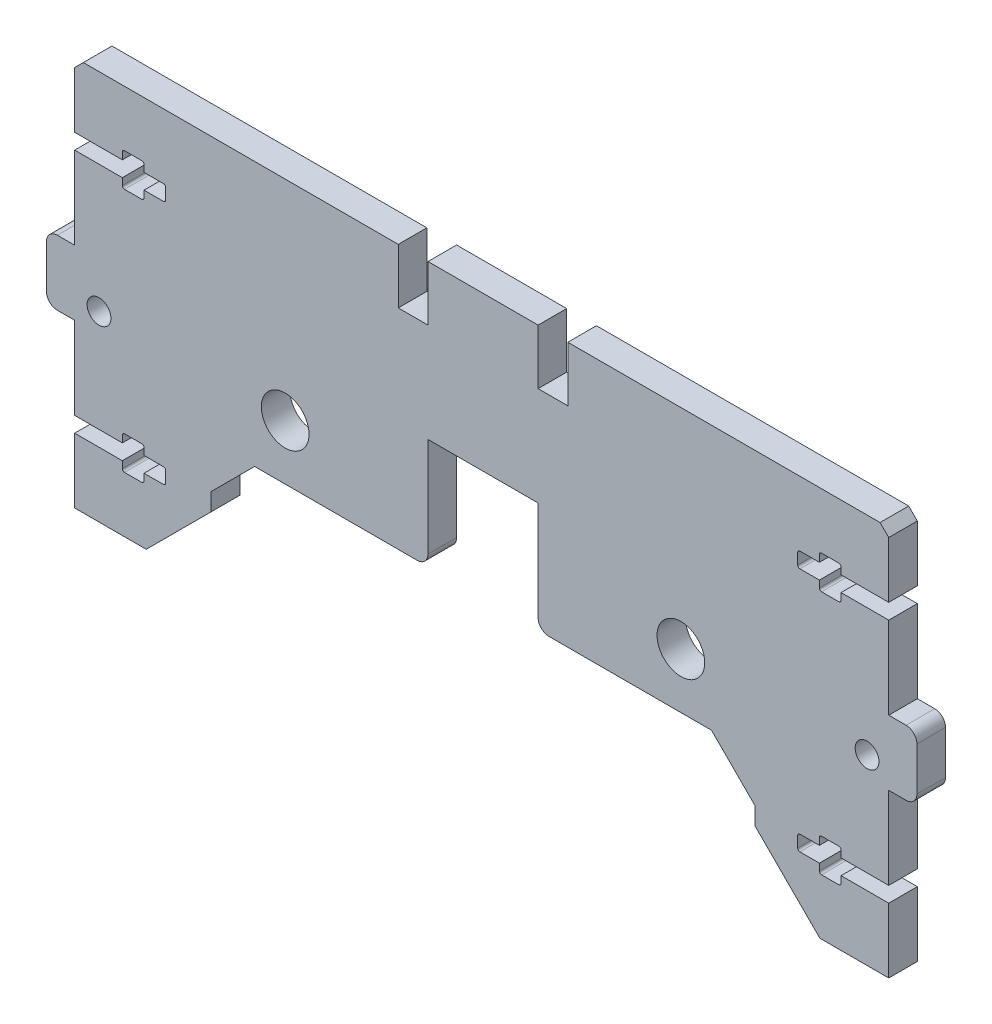
SolidWorks part; units mm, degrees
ref_plane "Front Plane" through (0, 0, 0) normal (0, 0, 1) x (1, 0, 0)
ref_plane "Top Plane" through (0, 0, 0) normal (0, 1, 0) x (1, 0, 0)
ref_plane "Right Plane" through (0, 0, 0) normal (1, 0, 0) x (0, 0, -1)
sketch "Model" plane through (0, 0, 0) normal (0, 0, 1) x (1, 0, 0)
  line L0 (146.91, 29.0548) -> (156.91, 19.0548)
  line L1 (146.91, 29.0548) -> (109.41, 29.0548)
  line L2 (106.91, 54.4548) -> (106.91, 31.5548)
  line L3 (81.51, 54.4548) -> (106.91, 54.4548)
  line L4 (81.51, 54.4548) -> (81.51, 31.5548)
  line L5 (79.01, 29.0548) -> (41.51, 29.0548)
  line L6 (31.51, 19.0548) -> (41.51, 29.0548)
  line L7 (31.51, 19.0548) -> (31.51, 15)
  line L8 (16.51, 0) -> (31.51, 15)
  line L9 (0, 0) -> (16.51, 0)
  line L10 (0, 14.95) -> (0, 0)
  line L11 (0, 14.95) -> (11, 14.95)
  line L12 (11, 14.95) -> (11, 13.365)
  line L13 (11.5, 12.865) -> (15.5, 12.865)
  line L14 (16, 13.365) -> (16, 14.95)
  line L15 (16, 14.95) -> (20.5, 14.95)
  line L16 (21, 15.45) -> (21, 18)
  line L17 (20.5, 18.5) -> (16, 18.5)
  line L18 (16, 18.5) -> (16, 20.085)
  line L19 (15.5, 20.585) -> (11.5, 20.585)
  line L20 (11, 20.085) -> (11, 18.5)
  line L21 (11, 18.5) -> (0, 18.5)
  line L22 (0, 37.5) -> (0, 18.5)
  line L23 (-4, 37.5) -> (0, 37.5)
  line L24 (-6.5, 50) -> (-6.5, 40)
  line L25 (0, 52.5) -> (-4, 52.5)
  line L26 (0, 71.5) -> (0, 52.5)
  line L27 (0, 71.5) -> (11, 71.5)
  line L28 (11, 71.5) -> (11, 69.915)
  line L29 (11.5, 69.415) -> (15.5, 69.415)
  line L30 (16, 69.915) -> (16, 71.5)
  line L31 (16, 71.5) -> (20.5, 71.5)
  line L32 (21, 72) -> (21, 74.55)
  line L33 (20.5, 75.05) -> (16, 75.05)
  line L34 (16, 75.05) -> (16, 76.635)
  line L35 (15.5, 77.135) -> (11.5, 77.135)
  line L36 (11, 76.635) -> (11, 75.05)
  line L37 (11, 75.05) -> (0, 75.05)
  line L38 (0, 88) -> (0, 75.05)
  line L39 (2, 90) -> (0, 88)
  line L40 (74.65, 90) -> (2, 90)
  line L41 (74.65, 77.3) -> (74.65, 90)
  line L42 (81.51, 77.3) -> (74.65, 77.3)
  line L43 (81.51, 77.3) -> (81.51, 90)
  line L44 (106.91, 90) -> (81.51, 90)
  line L45 (106.91, 77.3) -> (106.91, 90)
  line L46 (113.77, 77.3) -> (106.91, 77.3)
  line L47 (113.77, 90) -> (113.77, 77.3)
  line L48 (185.8, 90) -> (113.77, 90)
  line L49 (187.8, 88) -> (185.8, 90)
  line L50 (187.8, 75.05) -> (187.8, 88)
  line L51 (187.8, 75.05) -> (176.8, 75.05)
  line L52 (176.8, 75.05) -> (176.8, 76.635)
  line L53 (176.3, 77.135) -> (172.3, 77.135)
  line L54 (171.8, 76.635) -> (171.8, 75.05)
  line L55 (171.8, 75.05) -> (167.3, 75.05)
  line L56 (166.8, 74.55) -> (166.8, 72)
  line L57 (167.3, 71.5) -> (171.8, 71.5)
  line L58 (171.8, 71.5) -> (171.8, 69.915)
  line L59 (172.3, 69.415) -> (176.3, 69.415)
  line L60 (176.8, 69.915) -> (176.8, 71.5)
  line L61 (176.8, 71.5) -> (187.8, 71.5)
  line L62 (187.8, 52.5) -> (187.8, 71.5)
  line L63 (191.8, 52.5) -> (187.8, 52.5)
  line L64 (194.3, 40) -> (194.3, 50)
  line L65 (187.8, 18.5) -> (187.8, 37.5)
  line L66 (187.8, 18.5) -> (176.8, 18.5)
  line L67 (176.8, 18.5) -> (176.8, 20.085)
  line L68 (176.3, 20.585) -> (172.3, 20.585)
  line L69 (171.8, 20.085) -> (171.8, 18.5)
  line L70 (171.8, 18.5) -> (167.3, 18.5)
  line L71 (166.8, 18) -> (166.8, 15.45)
  line L72 (167.3, 14.95) -> (171.8, 14.95)
  line L73 (171.8, 14.95) -> (171.8, 13.365)
  line L74 (172.3, 12.865) -> (176.3, 12.865)
  line L75 (176.8, 13.365) -> (176.8, 14.95)
  line L76 (176.8, 14.95) -> (187.8, 14.95)
  line L77 (187.8, 0) -> (187.8, 14.95)
  line L78 (171.91, 0) -> (187.8, 0)
  line L79 (156.91, 15) -> (171.91, 0)
  line L80 (156.91, 15) -> (156.91, 19.0548)
  line L81 (187.8, 37.5) -> (191.8, 37.5)
  circle A0 centre (139.852, 41.7548) radius 5.5
  circle A1 centre (48.568, 41.7548) radius 5.5
  circle A2 centre (182.8, 42.08) radius 2.75
  circle A3 centre (5.62, 42.08) radius 2.75
  arc A4 (106.91, 31.5548) -> (109.41, 29.0548) centre (109.41, 31.5548) ccw
  arc A5 (79.01, 29.0548) -> (81.51, 31.5548) centre (79.01, 31.5548) ccw
  arc A6 (11, 13.365) -> (11.5, 12.865) centre (11.5, 13.365) ccw
  arc A7 (15.5, 12.865) -> (16, 13.365) centre (15.5, 13.365) ccw
  arc A8 (20.5, 14.95) -> (21, 15.45) centre (20.5, 15.45) ccw
  arc A9 (21, 18) -> (20.5, 18.5) centre (20.5, 18) ccw
  arc A10 (16, 20.085) -> (15.5, 20.585) centre (15.5, 20.085) ccw
  arc A11 (11.5, 20.585) -> (11, 20.085) centre (11.5, 20.085) ccw
  arc A12 (-6.5, 40) -> (-4, 37.5) centre (-4, 40) ccw
  arc A13 (-4, 52.5) -> (-6.5, 50) centre (-4, 50) ccw
  arc A14 (11, 69.915) -> (11.5, 69.415) centre (11.5, 69.915) ccw
  arc A15 (15.5, 69.415) -> (16, 69.915) centre (15.5, 69.915) ccw
  arc A16 (20.5, 71.5) -> (21, 72) centre (20.5, 72) ccw
  arc A17 (21, 74.55) -> (20.5, 75.05) centre (20.5, 74.55) ccw
  arc A18 (16, 76.635) -> (15.5, 77.135) centre (15.5, 76.635) ccw
  arc A19 (11.5, 77.135) -> (11, 76.635) centre (11.5, 76.635) ccw
  arc A20 (176.8, 76.635) -> (176.3, 77.135) centre (176.3, 76.635) ccw
  arc A21 (172.3, 77.135) -> (171.8, 76.635) centre (172.3, 76.635) ccw
  arc A22 (167.3, 75.05) -> (166.8, 74.55) centre (167.3, 74.55) ccw
  arc A23 (166.8, 72) -> (167.3, 71.5) centre (167.3, 72) ccw
  arc A24 (171.8, 69.915) -> (172.3, 69.415) centre (172.3, 69.915) ccw
  arc A25 (176.3, 69.415) -> (176.8, 69.915) centre (176.3, 69.915) ccw
  arc A26 (194.3, 50) -> (191.8, 52.5) centre (191.8, 50) ccw
  arc A27 (191.8, 37.5) -> (194.3, 40) centre (191.8, 40) ccw
  arc A28 (176.8, 20.085) -> (176.3, 20.585) centre (176.3, 20.085) ccw
  arc A29 (172.3, 20.585) -> (171.8, 20.085) centre (172.3, 20.085) ccw
  arc A30 (167.3, 18.5) -> (166.8, 18) centre (167.3, 18) ccw
  arc A31 (166.8, 15.45) -> (167.3, 14.95) centre (167.3, 15.45) ccw
  arc A32 (171.8, 13.365) -> (172.3, 12.865) centre (172.3, 13.365) ccw
  arc A33 (176.3, 12.865) -> (176.8, 13.365) centre (176.3, 13.365) ccw
extrude "Boss-Extrude1" add sketch "Model" along normal blind 6.6
